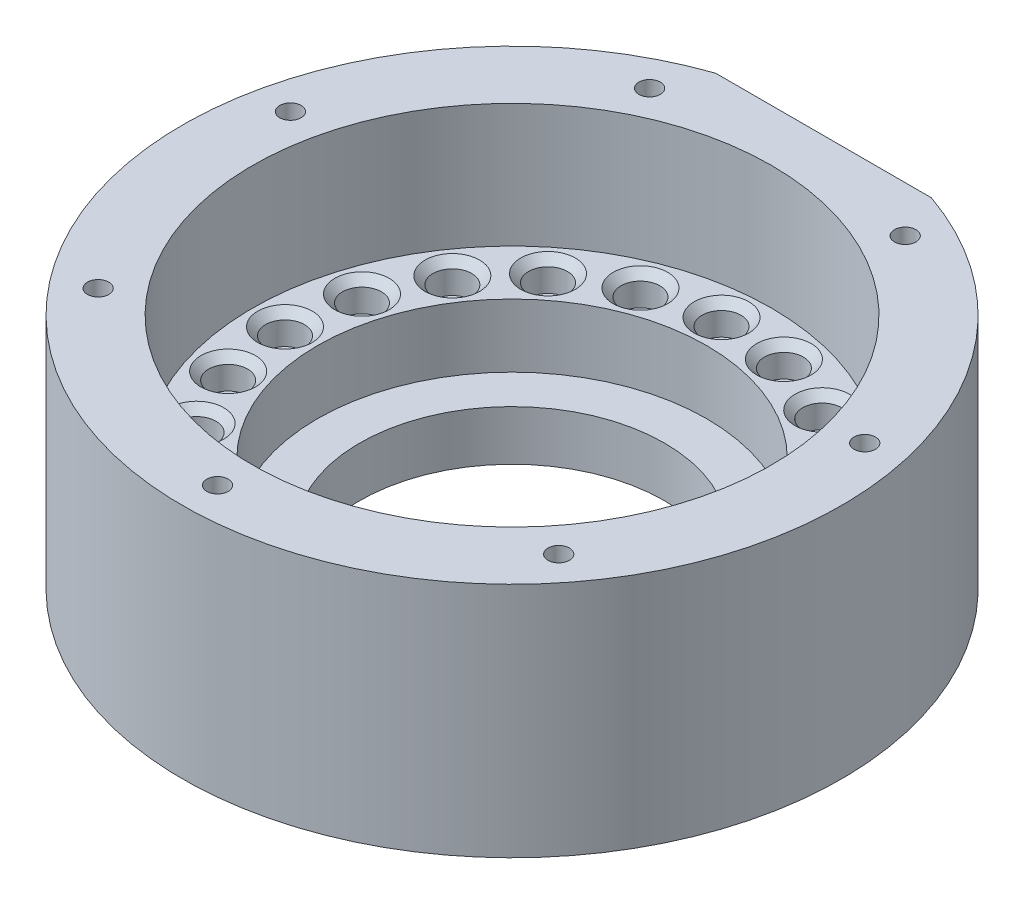
SolidWorks part; units mm, degrees
material "6061 Alloy"
ref_plane "Front Plane" through (0, 0, 0) normal (0, 0, 1) x (1, 0, 0)
ref_plane "Top Plane" through (0, 0, 0) normal (0, 1, 0) x (1, 0, 0)
ref_plane "Right Plane" through (0, 0, 0) normal (1, 0, 0) x (0, 0, -1)
sketch "Sketch1" plane through (0, 0, 0) normal (0, 1, 0) x (1, 0, 0)
  circle A0 centre (0, 0) radius 23.5
  circle A1 centre (0, 0) radius 50.8
  dimension "D1" = 101.6
  dimension "D2" = 47
extrude "Boss-Extrude1" add sketch "Sketch1" along normal blind 7.7 contours A0 | A1
sketch "Sketch3" plane through (0, 7.7, 0) normal (0, 1, 0) x (1, 0, 0)
  circle A0 centre (0, 0) radius 50.8
  circle A1 centre (0, 0) radius 30
  circle M4 centre (0, 0) radius 23.5
  dimension "D1" = 60
  dimension "D2" = 101.6
extrude "Boss-Extrude2" add sketch "Sketch3" along normal blind 9.7625 contours A1 M4 | A0
sketch "Sketch4" plane through (0, 17.4625, 0) normal (0, 1, 0) x (1, 0, 0)
  circle A0 centre (0, 0) radius 50.8
  circle A1 centre (0, 0) radius 40
  dimension "D1" = 80
  dimension "D2" = 101.6
extrude "Boss-Extrude3" add sketch "Sketch4" along normal blind 19.05
sketch "Sketch5" plane through (0, 17.4625, 0) normal (0, 1, 0) x (1, 0, 0)
  line L0 (0, 0) -> (-30, 0)
  line L1 (-20.0819, 0) -> (20.0819, 0) construction
  line L2 (-30, 0) -> (-40, 0)
  circle A0 centre (0, 0) radius 30 construction
  circle A1 centre (0, 0) radius 40 construction
  circle A2 centre (-35, 0) radius 3
  circle A3 centre (-33.445, 10.3164) radius 3
  circle A4 centre (-28.9184, 19.7162) radius 3
  circle A5 centre (-21.8221, 27.3641) radius 3
  circle A6 centre (-12.7869, 32.5806) radius 3
  circle A7 centre (-2.6156, 34.9021) radius 3
  circle A8 centre (7.7882, 34.1225) radius 3
  circle A9 centre (17.5, 30.3109) radius 3
  circle A10 centre (25.6568, 23.806) radius 3
  circle A11 centre (31.5339, 15.1859) radius 3
  circle A12 centre (34.6091, 5.2165) radius 3
  circle A13 centre (34.6091, -5.2165) radius 3
  circle A14 centre (31.5339, -15.1859) radius 3
  circle A15 centre (25.6568, -23.806) radius 3
  circle A16 centre (17.5, -30.3109) radius 3
  circle A17 centre (7.7882, -34.1225) radius 3
  circle A18 centre (-2.6156, -34.9021) radius 3
  circle A19 centre (-12.7869, -32.5806) radius 3
  circle A20 centre (-21.8221, -27.3641) radius 3
  circle A21 centre (-28.9184, -19.7162) radius 3
  circle A22 centre (-33.445, -10.3164) radius 3
  point P55 (0, 0)
  dimension "D1" = 6
  dimension "D2" = 21
extrude "Cut-Extrude1" cut sketch "Sketch5" against normal blind 4.7625 contours L2 A2 | L2 A2 | A3 | A4 | A5 | A6 | A7 | A8 | A9 | A10 | A11 | A12 | A13 | A14 | A16 | A17 | A18 | A19 | A20 | A21 | A22 | A15
chamfer "Chamfer1" distance 1.2 angle 45 21 edges at (-33.445, 17.4625, -7.3164) (-21.8221, 17.4625, -24.3641) (-28.9184, 17.4625, -16.7162) (-35, 17.4625, 3) (-33.445, 17.4625, 13.3164) (-28.9184, 17.4625, 22.7162) (-21.8221, 17.4625, 30.3641) (-12.7869, 17.4625, 35.5806) (-2.6156, 17.4625, 37.9021) (7.7882, 17.4625, 37.1225) (17.5, 17.4625, 33.3109) (25.6568, 17.4625, 26.806) (31.5339, 17.4625, 18.1859) (34.6091, 17.4625, 8.2165) (34.6091, 17.4625, -2.2165) (31.5339, 17.4625, -12.1859) (25.6568, 17.4625, -20.806) (17.5, 17.4625, -27.3109) (7.7882, 17.4625, -31.1225) (-2.6156, 17.4625, -31.9021) (-12.7869, 17.4625, -29.5806)
ref_plane "Plane1" through (0, 12.7, 0) normal (0, 1, 0) x (1, 0, 0)
sketch "Sketch6" plane through (0, 12.7, 0) normal (0, 1, 0) x (1, 0, 0)
  line L0 (-48, 0) -> (-35.3, 0)
  line L1 (-20.0819, 0) -> (20.0819, 0) construction
  line L2 (-35.3, 0) -> (-35.3, 50.8)
  line L3 (0, 50.8) -> (-35.3, 50.8)
  line L4 (0, -20.0819) -> (0, 20.0819) construction
  line L5 (-50.8, 0) -> (-50.8, 50.8)
  line L6 (-50.8, 50.8) -> (-35.3, 50.8)
  line L7 (-43.05, 50.8) -> (-43.05, 48)
  line L8 (0, 48) -> (-50.8, 48)
  line L9 (-43.05, 48) -> (-43.05, 0)
  line L10 (-35.3, 25.4) -> (-50.8, 25.4)
  line L11 (50.8, 0) -> (50.8, 50.8)
  line L12 (50.8, 50.8) -> (0, 50.8)
  line L13 (50.8, 50.8) -> (35.3, 50.8)
  line L14 (35.3, 50.8) -> (35.3, 0)
  line L15 (48, 0) -> (48, 50.8)
  line L16 (35.3, 25.4) -> (50.8, 25.4)
  line L17 (-48, 0) -> (-48, 50.8)
  circle A0 centre (0, 0) radius 48
  circle A1 centre (0, 0) radius 50.8 construction
  dimension "D1" = 96
  dimension "D2" = 12.7
  dimension "D3" = 12.7
sketch "Sketch8" plane through (0, 36.5125, 0) normal (0, 1, 0) x (1, 0, 0)
  line L0 (0, -40) -> (0, -50.8)
  line L1 (0, -20.0819) -> (0, 20.0819) construction
  line L2 (0, -50.8) -> (0, -40)
  line L3 (-39.717, -31.6733) -> (-31.2733, -24.9396)
  line L4 (-49.5263, 11.3041) -> (-38.9971, 8.9008)
  line L5 (-22.0413, 45.7692) -> (-17.3553, 36.0388)
  line L6 (22.0413, 45.7692) -> (17.3553, 36.0388)
  line L7 (49.5263, 11.3041) -> (38.9971, 8.9008)
  line L8 (39.717, -31.6733) -> (31.2733, -24.9396)
  line L9 (0, -40) -> (0, -50.8)
  circle A0 centre (0, 0) radius 40 construction
  point P22 (0, 0)
  point P23 (-44.2617, 10.1025)
  point P25 (-35.4951, -28.3064)
  point P27 (-19.6983, 40.904)
  point P29 (19.6983, 40.904)
  point P31 (44.2617, 10.1025)
  point P33 (35.4951, -28.3064)
  point P44 (0, -45.4)
  dimension "D2" = 7
sketch "Sketch9" plane through (0, 36.5125, 0) normal (0, 1, 0) x (1, 0, 0)
  line L0 (0, 48) -> (-63.5, 48)
  line L1 (0, 48) -> (63.5, 48)
  line L2 (63.5, 48) -> (63.5, 62.7356)
  line L3 (-63.5, 48) -> (-63.5, 62.7356)
  line L4 (-63.5, 62.7356) -> (63.5, 62.7356)
  line L5 (-63.5, 55.3678) -> (0, 55.3678)
  line L6 (0, -20.0819) -> (0, 20.0819) construction
  line L7 (0, 55.3678) -> (63.5, 55.3678)
  circle A0 centre (0, 0) radius 48
  arc M11 (35.3, 36.5315) -> (-35.3, 36.5315) centre (0, 0) ccw
  dimension "D1" = 96
  dimension "D2" = 127
extrude "Cut-Extrude4" cut sketch "Sketch9" against normal through all contours L0 L1 M11
hole_wizard "M4x0.7 Tapped Hole1" positions "Sketch8" profile "Sketch10" tap size "M4x0.7" standard "ANSI Metric" end condition up to next
sketch "Sketch10" plane through (0, 36.5125, 45.4) normal (1, 0, 0) x (0, 0, 1)
  line L0 (0, 0) -> (0, 36.5135)
  line L1 (0, 36.5135) -> (1.65, 36.5135)
  line L2 (1.65, 36.5135) -> (1.65, 0)
  line L5 (1.65, 0) -> (0, 0)
  line L11 (0, -6.35) -> (0, 107.95) construction
  dimension "Thru Tap Drill Dia." = 3.3
  dimension "Thru Tap Drill Depth" = 36.5135
cosmetic thread "Hole Thread1" parameters "D2"=4
cosmetic thread "Hole Thread2" parameters "D2"=4
cosmetic thread "Hole Thread3" parameters "D2"=4
cosmetic thread "Hole Thread4" parameters "D2"=4
cosmetic thread "Hole Thread5" parameters "D2"=4
cosmetic thread "Hole Thread6" parameters "D2"=4
cosmetic thread "Hole Thread7" parameters "D2"=4
